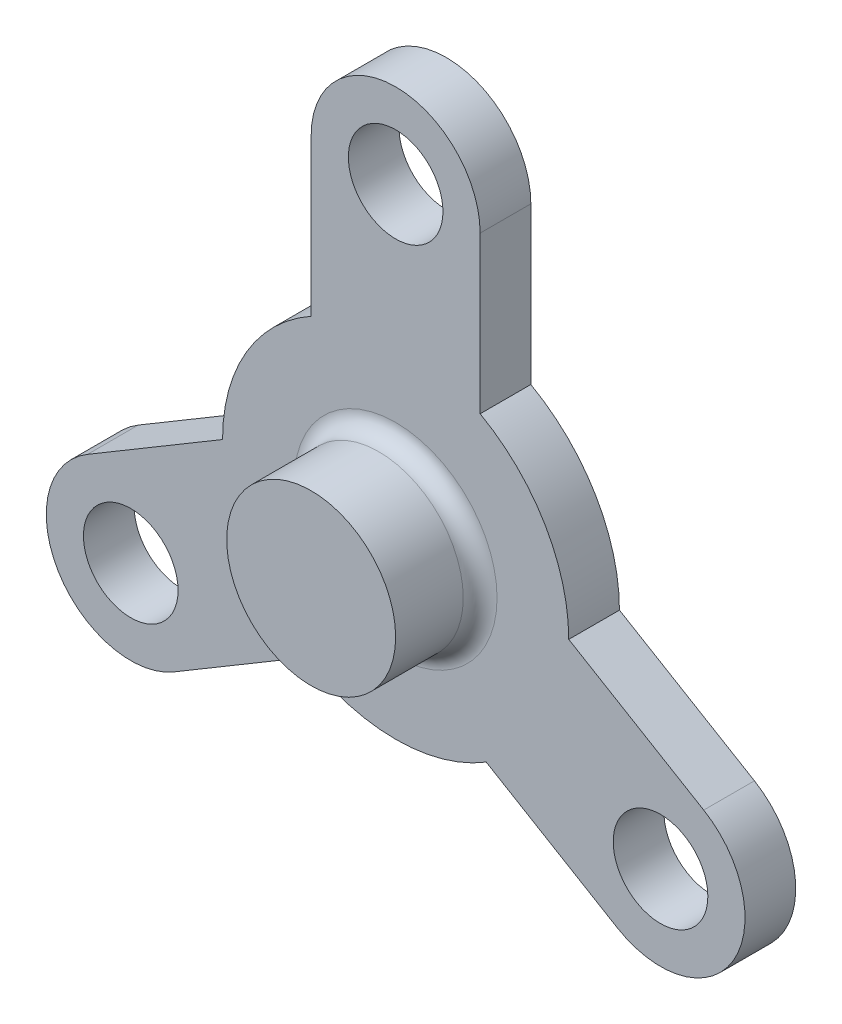
SolidWorks part; units mm, degrees
ref_plane "Alzado" through (0, 0, 0) normal (0, 0, 1) x (1, 0, 0)
ref_plane "Planta" through (0, 0, 0) normal (0, 1, 0) x (1, 0, 0)
ref_plane "Vista lateral" through (0, 0, 0) normal (1, 0, 0) x (0, 0, -1)
sketch "Croquis1" plane through (0, 0, 0) normal (0, 0, 1) x (1, 0, 0)
  line L0 (-18.2318, -4.7531) -> (-10.2435, 0)
  line L1 (-13.1183, -13.3469) -> (-5.359, -8.7299)
  line L2 (13.1183, -13.3469) -> (5.359, -8.7299)
  line L3 (-13.1183, -13.3469) -> (-18.2318, -4.7531)
  line L7 (13.1183, -13.3469) -> (18.2318, -4.7531)
  line L11 (-5, 18.2) -> (5, 18.2)
  line L15 (18.2318, -4.7531) -> (10.2435, 0)
  line L16 (-5, 18.2) -> (-5, 8.9404)
  line L17 (5, 18.2) -> (5, 8.9404)
  circle A0 centre (0, 18.2) radius 5
  circle A1 centre (15.6751, -9.05) radius 5
  circle A2 centre (-15.6751, -9.05) radius 5
  circle A3 centre (0, 0) radius 10.2435
  dimension "D7" = 10
  dimension "D8" = 10
  dimension "D9" = 10
  dimension "D1" = 90
  dimension "D2" = 90
  dimension "D3" = 90
  dimension "D4" = 18.1
  dimension "D5" = 18.1
  dimension "D6" = 18.2
  dimension "D10" = 90
  dimension "D11" = 90
  dimension "D12" = 90
extrude "Saliente-Extruir1" add sketch "Croquis1" along normal blind 3 contours L3 A2 | L3 A2 | A3 L0 A2 L1 | A3 | A3 L2 A1 L15 | A3 L17 A0 L16 | L11 A0 | L11 A0
sketch "Croquis2" plane through (0, 0, 3) normal (0, 0, 1) x (1, 0, 0)
  circle A0 centre (0, 18.2) radius 2.8
  circle A1 centre (15.6751, -9.05) radius 2.8
  circle A2 centre (-15.6751, -9.05) radius 2.8
  dimension "D1" = 5.6
  dimension "D2" = 5.6
  dimension "D3" = 5.6
extrude "Cortar-Extruir3" cut sketch "Croquis2" against normal blind 5.5
sketch "Croquis3" plane through (0, 0, 3) normal (0, 0, 1) x (1, 0, 0)
  circle A0 centre (0, 0) radius 5
  dimension "D1" = 10
extrude "Saliente-Extruir2" add sketch "Croquis3" along normal blind 5
fillet "Redondeo1" radius 1 1 edges at (5, 0, 3)
